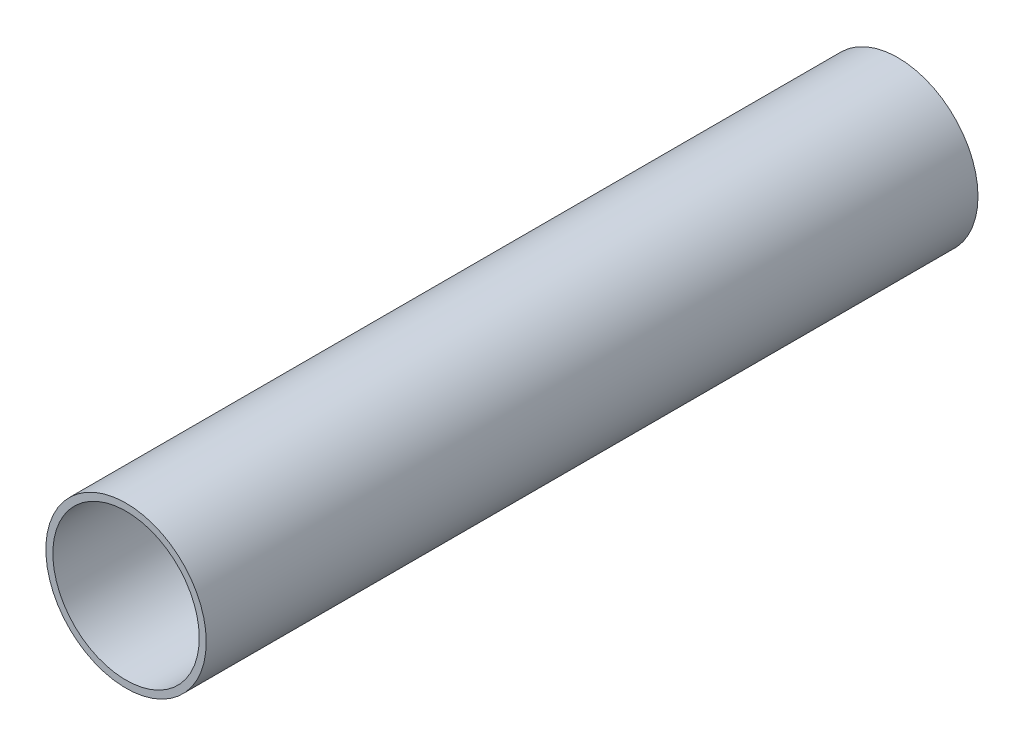
SolidWorks part; units mm, degrees
ref_plane "Front Plane" through (0, 0, 0) normal (0, 0, 1) x (1, 0, 0)
ref_plane "Top Plane" through (0, 0, 0) normal (0, 1, 0) x (1, 0, 0)
ref_plane "Right Plane" through (0, 0, 0) normal (1, 0, 0) x (0, 0, -1)
sketch "Sketch1" plane through (0, 0, 0) normal (0, 0, 1) x (1, 0, 0)
  circle A1 centre (0, 0) radius 34.925
  circle A2 centre (0, 0) radius 31.877
  dimension "D1" = 69.85
  dimension "D2" = 3.048
extrude "Boss-Extrude1" add sketch "Sketch1" along normal up to surface (336.0668 mm away)
